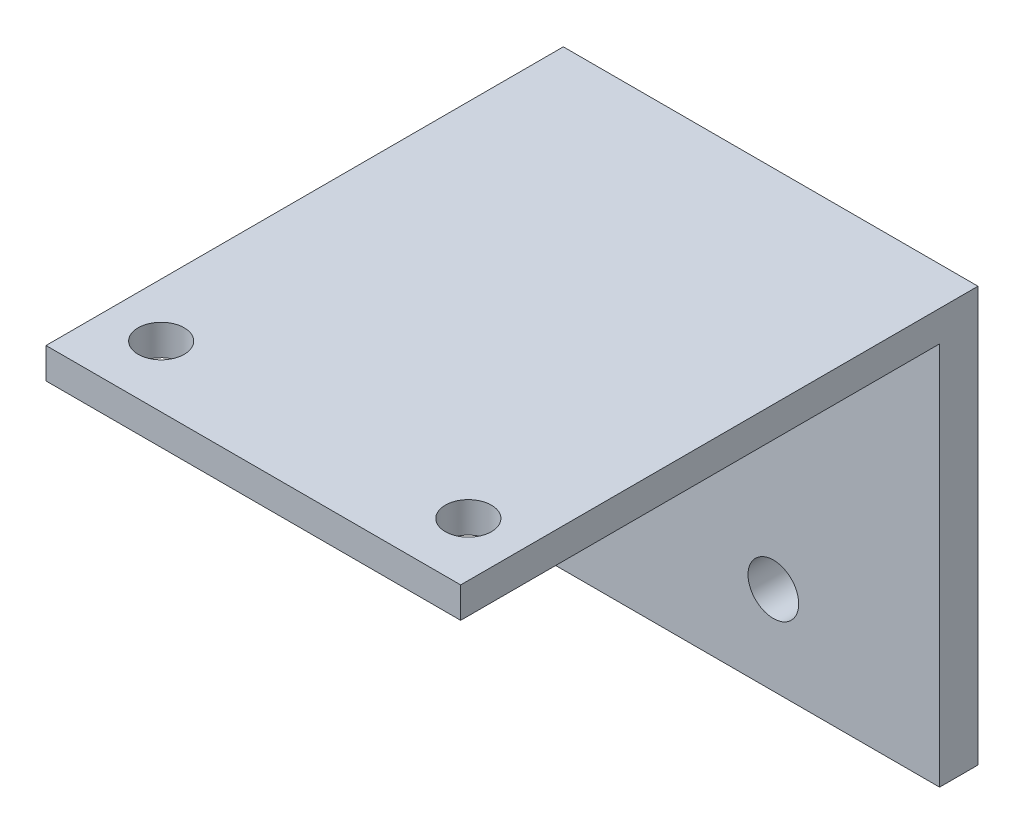
SolidWorks part; units mm, degrees
ref_plane "Plan de face" through (0, 0, 0) normal (0, 0, 1) x (1, 0, 0)
ref_plane "Plan de dessus" through (0, 0, 0) normal (0, 1, 0) x (1, 0, 0)
ref_plane "Plan de droite" through (0, 0, 0) normal (1, 0, 0) x (0, 0, -1)
sketch "Esquisse1" plane through (0, 0, 0) normal (0, 0, 1) x (1, 0, 0)
  line L1 (-27, -27) -> (27, -27)
  line L2 (-27, -27) -> (-27, 27)
  line L3 (-27, 27) -> (27, 27)
  line L4 (27, -27) -> (27, 27)
  line L5 (-27, -27) -> (27, 27) construction
  line L6 (-27, 27) -> (27, -27) construction
  line L7 (9, -27) -> (-9, -27)
  line L8 (9, -27) -> (9, 27)
  line L9 (9, 27) -> (-9, 27)
  line L10 (-9, -27) -> (-9, 27)
  line L11 (9, -27) -> (-9, 27) construction
  line L12 (9, 27) -> (-9, -27) construction
  circle A0 centre (-3.2581, 19) radius 3
  circle A1 centre (-3.2581, -21) radius 3
  point P0 (0, 0)
  point P7 (0, 0)
  dimension "D4" = 6
  dimension "D1" = 54
  dimension "D2" = 54
  dimension "D3" = 18
  dimension "D5" = 8
  dimension "D6" = 5.7419
  dimension "D7" = 2
extrude "Boss.-Extru.1" add sketch "Esquisse1" along normal blind 67.37 contours L8 L1 L4 L3 | L1 L10 L3 L2 | L10 L1 L8 L3 A1 A0
sketch "Esquisse2" plane through (0, 0, 67.37) normal (0, 0, 1) x (1, 0, 0)
  line L8 (23, 23) -> (-23, 23)
  line L9 (-23, 23) -> (-23, -23)
  line L10 (-23, -23) -> (23, -23)
  line L11 (23, -23) -> (23, 23)
  line L12 (38.775, 23) -> (-47.1129, 23)
  line L13 (-47.1129, 23) -> (-47.1129, -35.7903)
  line L14 (-47.1129, -35.7903) -> (38.775, -35.7903)
  line L15 (38.775, -35.7903) -> (38.775, 23)
  dimension "D1" = 4
extrude "Enlèv. mat.-Extru.1" cut sketch "Esquisse2" against normal blind 62.37
sketch "Esquisse3" plane through (0, 23, 0) normal (0, -1, 0) x (1, 0, 0)
  line L0 (27, 67.37) -> (-27, 67.37) construction
  line L1 (-27, 67.37) -> (-27, 5) construction
  circle A0 centre (-20, 59.37) radius 3
  circle A1 centre (20, 59.37) radius 3
  dimension "D3" = 6
  dimension "D1" = 8
  dimension "D2" = 7
  dimension "D4" = 2
extrude "Enlèv. mat.-Extru.2" cut sketch "Esquisse3" against normal blind 62.37
hole_wizard "Dégagement M61" positions "Esquisse5" profile "Esquisse4" hole size "M6" standard "JIS" end condition through all
sketch "Esquisse5" plane through (0, 0, 0) normal (0, 0, -1) x (-1, 0, 0)
  point P0 (-5.3523, -15.5)
  point P2 (-5.3523, 16.5)
sketch "Esquisse4" plane through (5.3523, -15.5, 0) normal (1, 0, 0) x (0, 1, 0)
  line L0 (0, 0) -> (0, 67.37)
  line L1 (0, 67.37) -> (3.3, 67.37)
  line L2 (3.3, 67.37) -> (3.3, 0)
  line L5 (3.3, 0) -> (0, 0)
  line L11 (0, -6.35) -> (0, 107.95) construction
  dimension "Diamètre du perçage jusqu'au prochain" = 6.6
  dimension "Profondeur du perçage jusqu'au prochain" = 67.37
